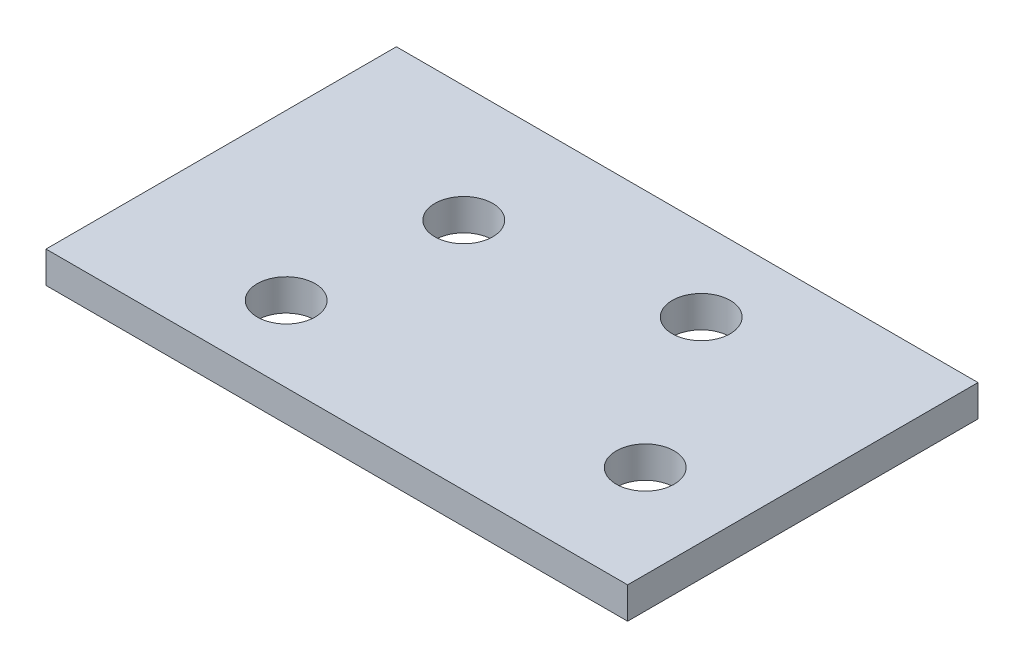
SolidWorks part; units mm, degrees
ref_plane "Front Plane" through (0, 0, 0) normal (0, 0, 1) x (1, 0, 0)
ref_plane "Top Plane" through (0, 0, 0) normal (0, 1, 0) x (1, 0, 0)
ref_plane "Right Plane" through (0, 0, 0) normal (1, 0, 0) x (0, 0, -1)
sketch "Sketch1" plane through (0, 0, 0) normal (0, 1, 0) x (1, 0, 0)
  line L0 (-12.5, 25) -> (12.5, -25) construction
  line L1 (-17.5, -27.5) -> (17.5, -27.5)
  line L2 (-17.5, -27.5) -> (-17.5, 27.5)
  line L3 (-17.5, 27.5) -> (17.5, 27.5)
  line L4 (17.5, -27.5) -> (17.5, 27.5)
  line L5 (17.5, 0) -> (-17.5, 0) construction
  line L6 (14.244, -20.9912) -> (15.2972, -20.9912)
  line L7 (-12.5, -25) -> (12.5, -25) construction
  line L8 (-12.5, -25) -> (-12.5, 25) construction
  line L9 (-12.5, 25) -> (12.5, 25) construction
  line L10 (12.5, -25) -> (12.5, 25) construction
  line L11 (14.244, -20.9912) -> (14.244, -22.8013)
  line L12 (14.244, -22.8013) -> (15.2972, -22.8013)
  line L13 (15.2972, -20.9912) -> (15.2972, -22.8013)
  line L14 (14.244, -20.9912) -> (15.2972, -22.8013) construction
  line L15 (14.244, -22.8013) -> (15.2972, -20.9912) construction
  circle A0 centre (12.5, 25) radius 1.5
  circle A1 centre (-12.5, 25) radius 1.5
  circle A2 centre (12.5, -25) radius 1.5
  circle A3 centre (-12.5, -25) radius 1.5
  point P0 (0, 0)
  point P6 (0, 0)
  point P25 (0, 27.5)
  point P26 (0, 25)
  point P27 (12.5, 0)
  point P28 (-17.5, 0)
  point P29 (14.7706, -21.8962)
  dimension "D3" = 3
  dimension "D1" = 25
  dimension "D2" = 50
  dimension "D13" = 35
  dimension "D14" = 55
extrude "Boss-Extrude1" add sketch "Sketch1" along normal blind 3
sketch "Sketch2" plane through (0, 3, 0) normal (0, 1, 0) x (1, 0, 0)
  line L1 (-13.6936, 9.1821) -> (16.4369, 9.1821)
  line L2 (-13.6936, 9.1821) -> (-13.6936, -8.9691)
  line L3 (-13.6936, -8.9691) -> (16.4369, -8.9691)
  line L4 (16.4369, 9.1821) -> (16.4369, -8.9691)
extrude "Boss-Extrude2" add sketch "Sketch2" along normal blind 11
sketch "Sketch4" plane through (0, 0, 0) normal (0, -1, 0) x (1, 0, 0)
  line L1 (14.2012, 8.8296) -> (-11.7715, 8.8296)
  line L2 (14.2012, 8.8296) -> (14.2012, -8.906)
  line L3 (14.2012, -8.906) -> (-11.7715, -8.906)
  line L4 (-11.7715, 8.8296) -> (-11.7715, -8.906)
extrude "Cut-Extrude2" cut sketch "Sketch4" against normal blind 4
sketch "Sketch6" plane through (0, 0, 0) normal (0, -1, 0) x (1, 0, 0)
  line L0 (-17.5, 0) -> (17.5, 0) construction
  line L5 (-17.5, -27.5) -> (-17.5, 27.5) construction
  line L14 (17.5, 27.5) -> (17.5, -27.5) construction
  line L15 (0, 27.7475) -> (0, -25.4862) construction
  line L16 (17.5, -27.5) -> (-17.5, -27.5) construction
  line L17 (-17.5, 27.5) -> (17.5, 27.5) construction
  line L18 (-17.5, -27.5) -> (-17.5, 27.5) construction
  circle A12 centre (11.63, 3.25) radius 1.5
  circle A13 centre (-5.17, 5.05) radius 1.5
  circle A14 centre (-4.17, -3.15) radius 1.5
  circle A15 centre (6.33, -4.95) radius 1.5
  point P0 (0, 0)
  point P11 (0, 0)
  point P23 (0, 0)
  dimension "D3" = 30.75
  dimension "D8" = 3
  dimension "D2" = 13.33
  dimension "D4" = 22.45
  dimension "D6" = 12.33
  dimension "D7" = 5.87
  dimension "D9" = 22.55
  dimension "D10" = 11.17
  dimension "D11" = 24.35
extrude "Cut-Extrude3" cut sketch "Sketch6" against normal through all both and the other way through all
sketch "Sketch7" plane through (0, 4, 0) normal (0, -1, 0) x (1, 0, 0)
  circle A0 centre (-5.17, 5.05) radius 3
  circle A1 centre (-4.17, -3.15) radius 3
  circle A2 centre (6.33, -4.95) radius 3
  circle A3 centre (11.63, 3.25) radius 3
  dimension "D1" = 6
extrude "Cut-Extrude4" cut sketch "Sketch7" against normal blind 2.5 and the other way through all
sketch "Sketch8" plane through (0, 0, 27.5) normal (0, 0, 1) x (1, 0, 0)
  line L1 (-24.2895, 12.3661) -> (24.2674, 12.3661)
  line L2 (-24.2895, 12.3661) -> (-24.2895, -1.4329)
  line L3 (-24.2895, -1.4329) -> (24.2674, -1.4329)
  line L4 (24.2674, 12.3661) -> (24.2674, -1.4329)
extrude "Cut-Extrude5" cut sketch "Sketch8" against normal through all
